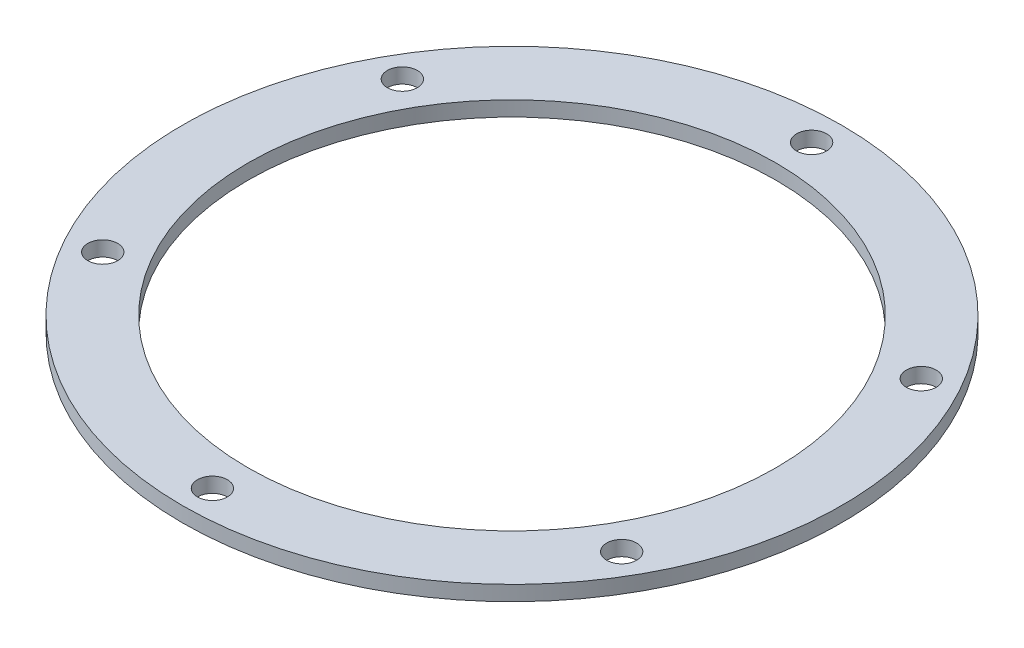
SolidWorks part; units mm, degrees
ref_plane "Front Plane" through (0, 0, 0) normal (0, 0, 1) x (1, 0, 0)
ref_plane "Top Plane" through (0, 0, 0) normal (0, 1, 0) x (1, 0, 0)
ref_plane "Right Plane" through (0, 0, 0) normal (1, 0, 0) x (0, 0, -1)
sketch "Sketch1" plane through (0, 0, 0) normal (0, 1, 0) x (1, 0, 0)
  circle A0 centre (0, 0) radius 44
  circle A1 centre (0, 0) radius 35.25
  circle A2 centre (0, 0) radius 40 construction
  circle A3 centre (0, 40) radius 2
  circle A4 centre (34.641, 20) radius 2
  circle A5 centre (34.641, -20) radius 2
  circle A6 centre (0, -40) radius 2
  circle A7 centre (-34.641, -20) radius 2
  circle A8 centre (-34.641, 20) radius 2
  point P16 (0, 0)
  dimension "D1" = 70.5
  dimension "D3" = 80
  dimension "D4" = 4
  dimension "D2" = 8.75
  dimension "D5" = 6
extrude "Boss-Extrude1" add sketch "Sketch1" along normal blind 2
equation "\"Ns\"= 18"
equation "\"Np\"= 45"
equation "\"Nr\"= 108"
equation "\"num_planet\"= 3"
equation "\"module\"= 0.7"
equation "\"pressure angle\"= 20.0deg"
equation "\"h_a\"= 0.7"
equation "\"h_b\"= 0.875"
equation "\"clr_tip_root\"= 0.17500000000000004"
equation "\"dp_s\"= 12.6"
equation "\"db_s\"= 11.840127021902445"
equation "\"fw_s_calc\"= 6.9645987548691926"
equation "\"alpha_s\"= 0.8539582918412556"
equation "\"beta_s\"= 8.292083416317489"
equation "\"dp_p\"= 31.499999999999996"
equation "\"db_p\"= 29.600317554756113"
equation "\"fw_p\"= 8.0"
equation "\"alpha_p\"= 0.8539582918412343"
equation "\"beta_p\"= 2.2920834163175314"
equation "\"pressure_angle\"= 20.0deg"
equation "\"h_f\"= 0.875"
equation "\"dp_r\"= 75.6"
equation "\"db_r\"= 71.04076213141467"
equation "\"fw_r\"= 8.0"
equation "\"alpha_r\"= 0.8539582918412449"
equation "\"beta_r\"= 3.374583250349157"
equation "\"bearing_ID\"= 55"
equation "\"bearing_OD\"= 72"
equation "\"bearing_height\"= 9"
equation "\"clearance_planet\"= 1.5"
equation "\"case_dist\"= 6.5"
equation "\"Motor_case_OD_max\"= 111.3"
equation "\"case_mounting_PCD\"= 103.8"
equation "\"bearing mount thickness\"= 8"
equation "\"case_mounting_hole_dia\"= 3"
equation "\"output_mounting_PCD\"= 80"
equation "\"output_mounting_hole_dia\"= 4"
equation "\"clearance_case_mount_holes_shell_thickness\"= 1"
equation "\"motor_case_OD_base\"= 101.8"
equation "\"sec_carrier_thickness\"= 5"
equation "\"sun_coupler_hub_thickness\"= 4"
equation "\"clearance_sun_coupler_sec_carrier\"= 1.5"
equation "\"clearance_motor_and_case\"= 5"
equation "\"motor_OD\"= 86.8"
equation "\"Motor_case_thickness\"= 2.5"
equation "\"Motor_case_ID\"= 96.8"
equation "\"case_mounting_hole_shift\"= 1.0"
equation "\"output_mounting_nut_wrench_size\"= 7"
equation "\"output_mounting_nut_thickness\"= 3.2"
equation "\"case_mounting_hole_allen_socket_dia\"= 5.5"
equation "\"output_mounting_nut_depth\"= 3"
equation "\"case_mounting_bolt_depth\"= 4.5"
equation "\"ring_radial_thickness\"= 5.0"
equation "\"ring_OD\"= 85.6"
equation "\"ring_to_chamfer_clearance\"= 2"
equation "\"Motor_case_OD_base_to_chamfer\"= 5"
equation "\"pattern_offset_from_motor_case_OD_base\"= 3"
equation "\"pattern_bulge_dia\"= 3"
equation "\"pattern_num_bulge\"= 18"
equation "\"pattern_depth\"= 2"
equation "\"motor_height\"= 26.5"
equation "\"case_mounting_wrench_size\"= 5.5"
equation "\"case_mounting_nut_clearance\"= 2"
equation "\"base_plate_thickness\"= 4"
equation "\"case_mounting_nut_thickness\"= 2.4"
equation "\"case_mounting_surface_height\"= 4"
equation "\"motor_mount_hole_PCD\"= 32"
equation "\"motor_mount_hole_dia\"= 4"
equation "\"motor_mount_hole_num\"= 4"
equation "\"central_hole_offset_from_motor_mount_PCD\"= 5"
equation "\"wire_slot_dist_from_center\"= 30"
equation "\"wire_slot_length\"= 10"
equation "\"wire_slot_radius\"= 4"
equation "\"driver_upper_holes_dist_from_center\"= 23"
equation "\"driver_lower_holes_dist_from_center\"= 15"
equation "\"driver_side_holes_dist_from_center\"= 20"
equation "\"driver_mount_holes_dia\"= 2.5"
equation "\"driver_mount_inserts_OD\"= 3.5"
equation "\"driver_mount_thickness\"= 1.5"
equation "\"driver_mount_height\"= 4"
equation "\"air_flow_hole_offset\"= 3"
equation "\"planet_pin_bolt_dia\"= 5"
equation "\"planet_pin_socket_head_dia\"= 8.5"
equation "\"carrier_PCD\"= 44.099999999999994"
equation "\"planet_shaft_dia\"= 8"
equation "\"planet_shaft_step_offset\"= 1"
equation "\"carrier_trapezoidal_support_sun_offset\"= 5"
equation "\"carrier_trapezoidal_support_hole_PCD_offset_bearing_ID\"= 4"
equation "\"carrier_trapezoidal_support_hole_dia\"= 3"
equation "\"carrier_trapezoidal_support_hole_socket_head_dia\"= 5.5"
equation "\"carrier_bearing_step_width\"= 1.5"
equation "\"standard_clearance_1_5mm\"= 1.5"
equation "\"standard_fillet_1_5mm\"= 1.5"
equation "\"sun_shaft_bearing_OD\"= 16"
equation "\"sun_shaft_bearing_width\"= 5"
equation "\"standard_bearing_insertion_chamfer\"= 0.5"
equation "\"carrier_trapezoidal_support_hole_wrench_size\"= 5.5"
equation "\"planet_pin_bolt_wrench_size\"= 8"
equation "\"planet_bearing_OD\"= 12"
equation "\"planet_bearing_width\"= 3.5"
equation "\"planet_bore\"= 10"
equation "\"motor_output_hole_PCD\"= 23"
equation "\"motor_output_hole_dia\"= 4"
equation "\"motor_output_hole_num\"= 4"
equation "\"sun_shaft_bearing_ID\"= 8"
equation "\"sun_hub_dia\"= 33.0"
equation "\"sun_central_bolt_dia\"= 5"
equation "\"sun_central_bolt_socket_head_dia\"= 8.5"
equation "\"fw_s_used\"= 16.0"
equation "\"motor_output_hole_CSK_OD\"= 8"
equation "\"motor_output_hole_CSK_head_height\"= 2.0"
equation "\"D1@Sketch1\"=\"bearing_OD\"-\"standard_clearance_1_5mm\""
equation "\"D2@Sketch1\"=\"bearing mount thickness\"+\"standard_clearance_1_5mm\"/2"
equation "\"D3@Sketch1\"=\"output_mounting_PCD\""
equation "\"D4@Sketch1\"=\"output_mounting_hole_dia\""
equation "\"bearing_retainer_thickness\"= 2"
equation "\"D1@Boss-Extrude1\"=\"bearing_retainer_thickness\""
